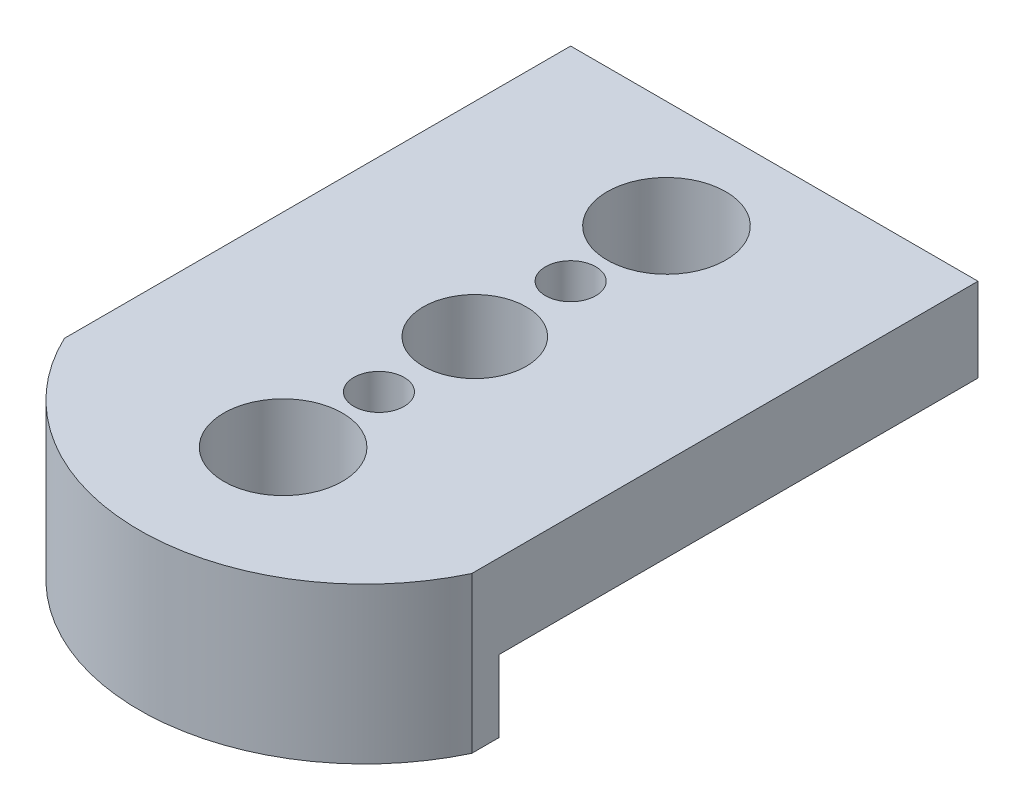
SolidWorks part; units mm, degrees
ref_plane "Front Plane" through (0, 0, 0) normal (0, 0, 1) x (1, 0, 0)
ref_plane "Top Plane" through (0, 0, 0) normal (0, 1, 0) x (1, 0, 0)
ref_plane "Right Plane" through (0, 0, 0) normal (1, 0, 0) x (0, 0, -1)
sketch "Sketch1" plane through (0, 0, 0) normal (0, 1, 0) x (1, 0, 0)
  line L1 (-17, -29) -> (17, -29)
  line L2 (-17, -29) -> (-17, 29)
  line L3 (-17, 29) -> (17, 29)
  line L4 (17, -29) -> (17, 29)
  line L5 (-17, -29) -> (17, 29) construction
  line L6 (-17, 29) -> (17, -29) construction
  point P0 (0, 0)
  dimension "D1" = 58
  dimension "D2" = 34
extrude "Boss-Extrude1" add sketch "Sketch1" along normal blind 13
sketch "Sketch3" plane through (0, 0, 0) normal (1, 0, 0) x (0, 0, -1)
  line L0 (-17, 13) -> (-12.05, 13)
  line L1 (29, 13) -> (-29, 13) construction
  line L2 (-17, 13) -> (-17, 0) construction
  line L3 (29, 0) -> (-29, 0) construction
  line L4 (-17, 0) -> (-10.6, 0)
  line L5 (-10.6, 0) -> (-10.6, 2.6)
  line L6 (-10.6, 2.6) -> (-12.05, 2.6)
  line L7 (-12.05, 2.6) -> (-12.05, 13)
  line L8 (-29, 13) -> (-29, 0) construction
  line L9 (-17, 13) -> (-17, 0)
  line L10 (13, 13) -> (13, 0)
  line L11 (-29, 13) -> (29, 13) construction
  line L12 (-29, 0) -> (29, 0) construction
  line L13 (13, 13) -> (17.95, 13)
  line L14 (17.95, 13) -> (17.95, 2.6)
  line L15 (17.95, 2.6) -> (19.4, 2.6)
  line L16 (19.4, 2.6) -> (19.4, 0)
  line L17 (19.4, 0) -> (13, 0)
  dimension "D1" = 4.95
  dimension "D2" = 6.4
  dimension "D3" = 12
  dimension "D4" = 2.6
  dimension "D5" = 30
  dimension "D6" = 6.4
  dimension "D7" = 2.6
  dimension "D8" = 4.95
revolve "Cut-Revolve1" cut sketch "Sketch3" angle 360 about L2
sketch "Sketch4" plane through (0, 0, 0) normal (0, -1, 0) x (1, 0, 0)
  line L0 (17, -29) -> (-17, -29) construction
  line L1 (3.7095, -5.425) -> (7.419, 1)
  line L2 (7.419, 1) -> (3.7095, 7.425)
  line L3 (3.7095, 7.425) -> (-3.7095, 7.425)
  line L4 (-3.7095, 7.425) -> (-7.419, 1)
  line L5 (-7.419, 1) -> (-3.7095, -5.425)
  line L6 (-3.7095, -5.425) -> (3.7095, -5.425)
  line L7 (-17, 29) -> (17, 29) construction
  circle A0 centre (0, 1) radius 6.425 construction
  circle A1 centre (0, 17) radius 4.95 construction
  point P13 (0, 29)
  dimension "D2" = 16
  dimension "D1" = 12.85
extrude "Cut-Extrude1" cut sketch "Sketch4" against normal blind 2.7
sketch "Sketch5" plane through (0, 2.7, 0) normal (0, -1, 0) x (1, 0, 0)
  line L0 (17, -29) -> (-17, -29) construction
  circle A0 centre (0, 1) radius 4.3
  point P9 (0, -29)
  dimension "D1" = 8.6
extrude "Cut-Extrude2" cut sketch "Sketch5" against normal through all
sketch "Sketch6" plane through (0, 0, -29) normal (0, 0, -1) x (-1, 0, 0)
  line L0 (-17, 6) -> (-14, 6)
  line L1 (-17, 13) -> (-17, 0) construction
  line L2 (-14, 6) -> (-14, 9)
  line L3 (-14, 9) -> (-6.6994, 9)
  line L4 (-6.6994, 9) -> (-8.8, 6)
  line L5 (-8.8, 6) -> (-8.8, 0)
  line L6 (-17, 0) -> (17, 0) construction
  line L7 (-8.8, 0) -> (-17, 0)
  line L8 (-17, 0) -> (-17, 6)
  line L9 (0, 0) -> (0, 13) construction
  line L10 (-17, 13) -> (17, 13) construction
  line L11 (8.8, 0) -> (17, 0)
  line L12 (8.8, 6) -> (8.8, 0)
  line L13 (6.6994, 9) -> (8.8, 6)
  line L14 (14, 9) -> (6.6994, 9)
  line L15 (14, 6) -> (14, 9)
  line L16 (17, 6) -> (14, 6)
  line L17 (17, 0) -> (17, 6)
  dimension "D1" = 6
  dimension "D2" = 55
  dimension "D3" = 3
  dimension "D4" = 3
  dimension "D5" = 8.2
extrude "Cut-Extrude3" cut sketch "Sketch6" against normal blind 45
sketch "Sketch7" plane through (0, 13, 0) normal (0, 1, 0) x (1, 0, 0)
  line L0 (17, -29) -> (17, 29) construction
  line L1 (-17, 29) -> (-17, -29) construction
  line L2 (17, -18.2533) -> (17, -29)
  line L3 (17, -29) -> (-17, -29)
  line L4 (-17, -29) -> (-17, -18.2533)
  arc A0 (17, -18.2533) -> (-17, -18.2533) centre (0, -10.1806) cw
  line M4 (17, -29) -> (17, 29)
  line M6 (-17, 29) -> (-17, -29)
  line M7 (-17, -29) -> (17, -29)
extrude "Cut-Extrude4" cut sketch "Sketch7" against normal through all contours A0 L3 M4 | A0 M7 M6
sketch "Sketch11" plane through (0, 0, 0) normal (1, 0, 0) x (0, 0, -1)
  line L0 (15, 13) -> (-1, 13)
  line L1 (-18.2533, 13) -> (29, 13) construction
  line L2 (15, 0) -> (15, 13)
  line L3 (29, 13) -> (-18.2533, 13) construction
  line L4 (15, 13) -> (19.95, 13)
  line L5 (15, 0) -> (21.4, 0)
  line L6 (-16, 0) -> (29, 0) construction
  line L7 (21.4, 0) -> (21.4, 2.6)
  line L8 (21.4, 2.6) -> (19.95, 2.6)
  line L9 (19.95, 2.6) -> (19.95, 13)
  line L10 (3.3, 13) -> (-5.3, 13) construction
  line L11 (-1, 0) -> (-1, 13)
  dimension "D1" = 16
  dimension "D2" = 4.95
  dimension "D3" = 2.6
  dimension "D4" = 6.4
revolve "Cut-Revolve2" cut sketch "Sketch11" angle 360 about L2
sketch "Sketch9" plane through (0, 0, 0) normal (0, -1, 0) x (1, 0, 0)
  line L0 (8.8, -29) -> (-8.8, -29) construction
  circle A0 centre (0, -7) radius 1.1
  circle A1 centre (0, 9) radius 1.1
  dimension "D2" = 2.2
  dimension "D3" = 2.2
  dimension "D1" = 22
  dimension "D4" = 38
extrude "Cut-Extrude5" cut sketch "Sketch9" against normal blind 13
sketch "Sketch10" plane through (0, 13, 0) normal (0, 1, 0) x (1, 0, 0)
  circle A0 centre (0, 7) radius 2.1
  circle A1 centre (0, -9) radius 2.1
  dimension "D1" = 4.2
  dimension "D2" = 4.2
extrude "Cut-Extrude6" cut sketch "Sketch10" against normal blind 3
sketch "Sketch12" plane through (0, 13, 0) normal (0, 1, 0) x (1, 0, 0)
  line L0 (17, -18.2533) -> (17, 29) construction
  line L1 (-17, 29) -> (17, 29)
  line L2 (-17, 29) -> (-17, 24)
  line L3 (-17, 24) -> (17, 24)
  line L4 (17, 29) -> (17, 24)
  dimension "D1" = 5
extrude "Cut-Extrude7" cut sketch "Sketch12" against normal blind 15
equation "\"2mmmm\"=13"
